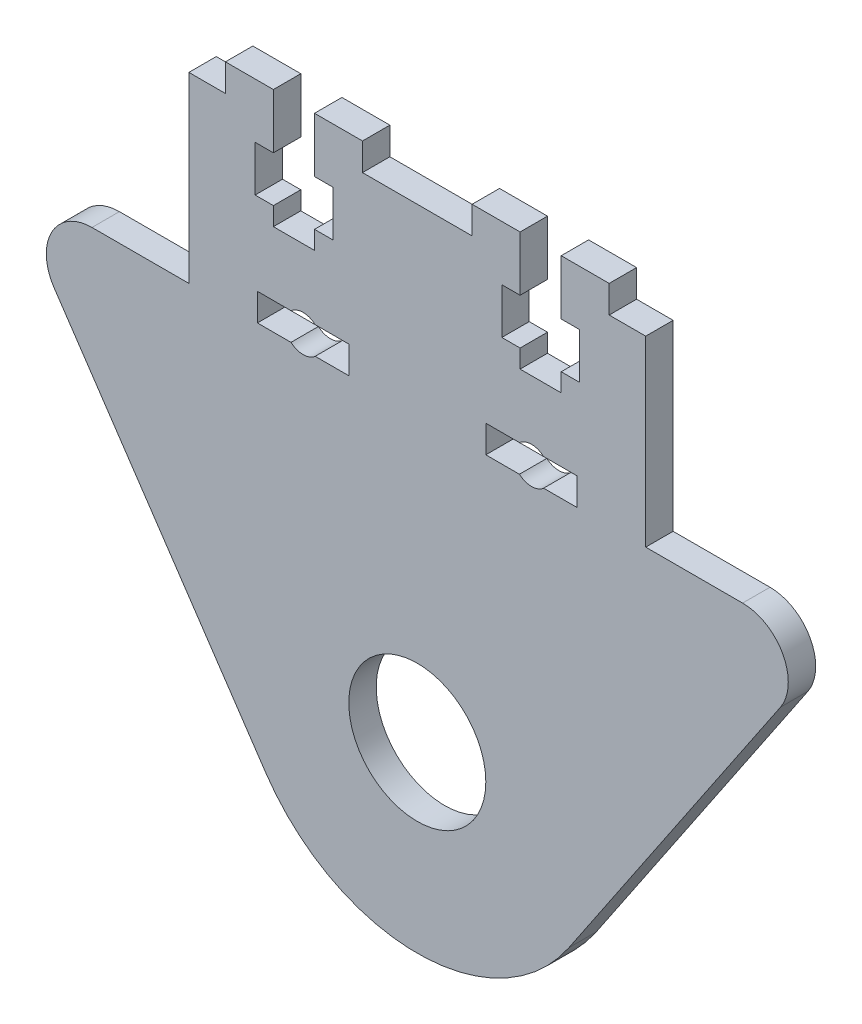
SolidWorks part; units mm, degrees
ref_plane "前视基准面" through (0, 0, 0) normal (0, 0, 1) x (1, 0, 0)
ref_plane "上视基准面" through (0, 0, 0) normal (0, 1, 0) x (1, 0, 0)
ref_plane "右视基准面" through (0, 0, 0) normal (1, 0, 0) x (0, 0, -1)
sketch "草图1" plane through (0, 0, 0) normal (0, 0, 1) x (1, 0, 0)
  line L0 (-45, 31) -> (45, 31)
  line L1 (-45, 31) -> (-16.587, -11.1746)
  line L2 (0, -1000) -> (0, 49000) construction
  line L3 (45, 31) -> (16.587, -11.1746)
  line L5 (-25, 31) -> (25, 31)
  line L6 (-25, 31) -> (-25, 51)
  line L7 (-25, 51) -> (25, 51)
  line L8 (25, 31) -> (25, 51)
  circle A0 centre (0, 0) radius 20
  circle A1 centre (0, 0) radius 7.5
  point P5 (0, 31)
  dimension "D1" = 40
  dimension "D2" = 90
  dimension "D3" = 31
  dimension "D4" = 15
  dimension "D5" = 20
  dimension "D6" = 50
  dimension "D7" = 25
extrude "凸台-拉伸1" add sketch "草图1" along normal blind 3 contours A0 L2 A1 | L2 A0 A1 | L2 A0 L3 L0 L5 | A0 L2 L0 L1 | L0 L2 L7 L6 | L2 L5 L8 L7
fillet "圆角1" radius 5 2 edges at (45, 31, 1.5) (-45, 31, 1.5)
sketch "草图2" plane through (0, 0, 3) normal (0, 0, 1) x (1, 0, 0)
  line L0 (-35.6027, 31) -> (-25, 31) construction
  line L1 (-17.5, 34) -> (-13.8229, 34)
  line L2 (-17.5, 34) -> (-17.5, 31)
  line L3 (-17.5, 31) -> (-13.8229, 31)
  line L4 (-7.5, 34) -> (-7.5, 31)
  line L5 (-17.5, 34) -> (-7.5, 31) construction
  line L6 (-17.5, 31) -> (-7.5, 34) construction
  line L7 (7.5, 34) -> (11.1771, 34)
  line L8 (7.5, 34) -> (7.5, 31)
  line L9 (7.5, 31) -> (11.1771, 31)
  line L10 (17.5, 34) -> (17.5, 31)
  line L11 (7.5, 34) -> (17.5, 31) construction
  line L12 (7.5, 31) -> (17.5, 34) construction
  line L13 (-11.1771, 31) -> (-7.5, 31)
  line L14 (-11.1771, 34) -> (-7.5, 34)
  line L15 (13.8229, 34) -> (17.5, 34)
  line L16 (13.8229, 31) -> (17.5, 31)
  arc A0 (-13.8229, 31) -> (-11.1771, 31) centre (-12.5, 32.5) ccw
  arc A1 (11.1771, 31) -> (13.8229, 31) centre (12.5, 32.5) ccw
  arc A2 (-11.1771, 34) -> (-13.8229, 34) centre (-12.5, 32.5) ccw
  arc A3 (13.8229, 34) -> (11.1771, 34) centre (12.5, 32.5) ccw
  point P0 (-12.5, 32.5)
  point P5 (12.5, 32.5)
  dimension "D7" = 4
  dimension "D8" = 4
  dimension "D1" = 3
  dimension "D2" = 10
  dimension "D3" = 3
  dimension "D4" = 10
  dimension "D5" = 7.5
  dimension "D6" = 7.5
extrude "切除-拉伸1" cut sketch "草图2" against normal blind 3
sketch "草图3" plane through (0, 0, 3) normal (0, 0, 1) x (1, 0, 0)
  line L0 (-25, 51) -> (25, 51) construction
  line L1 (-21, 51) -> (-6, 51)
  line L2 (-21, 51) -> (-21, 54)
  line L3 (-21, 54) -> (-6, 54)
  line L4 (-6, 51) -> (-6, 54)
  line L5 (-25, 31) -> (-25, 51) construction
  line L6 (21, 51) -> (6, 51)
  line L7 (21, 51) -> (21, 54)
  line L8 (21, 54) -> (6, 54)
  line L9 (6, 51) -> (6, 54)
  line L10 (25, 31) -> (25, 51) construction
  dimension "D1" = 3
  dimension "D2" = 15
  dimension "D3" = 3
  dimension "D4" = 15
  dimension "D5" = 4
  dimension "D6" = 3
  dimension "D7" = 4
extrude "凸台-拉伸2" add sketch "草图3" against normal blind 3
sketch "草图4" plane through (0, 0, 3) normal (0, 0, 1) x (1, 0, 0)
  line L0 (-15.75, 54) -> (-15.75, 48)
  line L1 (-6, 54) -> (-21, 54) construction
  line L2 (-15.75, 48) -> (-17.75, 48)
  line L3 (-17.75, 48) -> (-17.75, 43)
  line L4 (-17.75, 43) -> (-15.75, 43)
  line L5 (-15.75, 43) -> (-15.75, 41)
  line L6 (-15.75, 41) -> (-11.25, 41)
  line L7 (-11.25, 41) -> (-11.25, 43)
  line L8 (-11.25, 43) -> (-9.25, 43)
  line L9 (-9.25, 43) -> (-9.25, 48)
  line L10 (-9.25, 48) -> (-11.25, 48)
  line L11 (-11.25, 48) -> (-11.25, 54)
  line L12 (-11.25, 54) -> (-15.75, 54)
  line L13 (-21, 54) -> (-21, 51) construction
  line L14 (0, 51) -> (0, 0) construction
  line L15 (-6, 51) -> (6, 51) construction
  line L16 (11.25, 48) -> (11.25, 54)
  line L17 (9.25, 48) -> (11.25, 48)
  line L18 (9.25, 43) -> (9.25, 48)
  line L19 (11.25, 43) -> (9.25, 43)
  line L20 (11.25, 41) -> (11.25, 43)
  line L21 (15.75, 41) -> (11.25, 41)
  line L22 (15.75, 43) -> (15.75, 41)
  line L23 (17.75, 43) -> (15.75, 43)
  line L24 (17.75, 48) -> (17.75, 43)
  line L25 (15.75, 48) -> (17.75, 48)
  line L26 (15.75, 54) -> (15.75, 48)
  line L27 (11.25, 54) -> (15.75, 54)
  dimension "D1" = 6
  dimension "D2" = 2
  dimension "D3" = 5
  dimension "D4" = 2
  dimension "D5" = 2
  dimension "D6" = 4.5
  dimension "D7" = 2
  dimension "D8" = 2
  dimension "D9" = 5
  dimension "D10" = 2
  dimension "D11" = 5.25
extrude "切除-拉伸2" cut sketch "草图4" against normal blind 3
